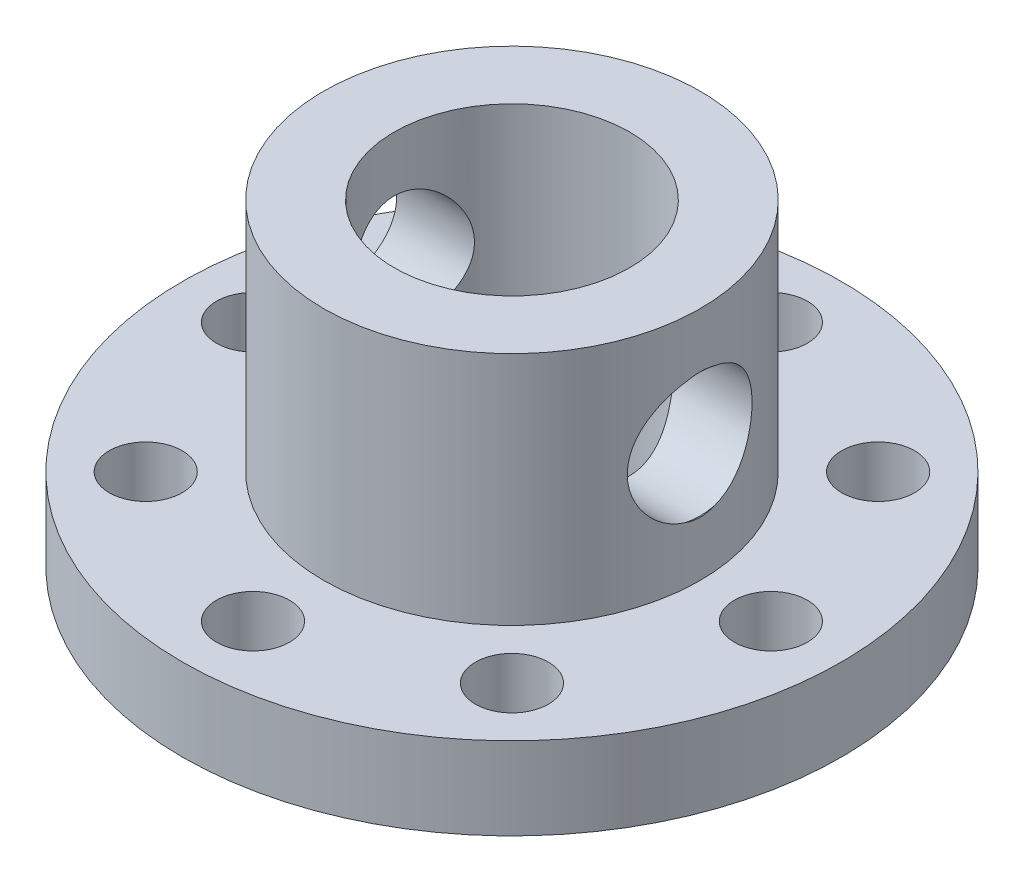
SolidWorks part; units mm, degrees
material "6061 Alloy"
ref_plane "Front Plane" through (0, 0, 0) normal (0, 0, 1) x (1, 0, 0)
ref_plane "Top Plane" through (0, 0, 0) normal (0, 1, 0) x (1, 0, 0)
ref_plane "Right Plane" through (0, 0, 0) normal (1, 0, 0) x (0, 0, -1)
sketch "Sketch1" plane through (0, 0, 0) normal (0, 1, 0) x (1, 0, 0)
  circle A0 centre (0, 0) radius 14
  dimension "D1" = 28
extrude "Boss-Extrude1" add sketch "Sketch1" along normal mid plane 3.5 contours A0
sketch "Sketch2" plane through (0, 1.75, 0) normal (0, 1, 0) x (1, 0, 0)
  line L0 (2.7822, 0.7455) -> (2.5435, 0.3349)
  line L1 (2.5435, 0.3349) -> (2.8804, 0)
  line L2 (2.8804, 0) -> (2.5435, -0.3349)
  line L3 (2.7822, -0.7455) -> (2.5435, -0.3349)
  line L4 (2.7822, -0.7455) -> (2.3701, -0.9817)
  line L5 (2.4945, -1.4402) -> (2.3701, -0.9817)
  line L6 (2.4945, -1.4402) -> (2.0353, -1.5617)
  line L7 (2.0367, -2.0367) -> (2.0353, -1.5617)
  line L8 (2.0367, -2.0367) -> (1.5617, -2.0353)
  line L9 (1.4402, -2.4945) -> (1.5617, -2.0353)
  line L10 (1.4402, -2.4945) -> (0.9817, -2.3701)
  line L11 (0.7455, -2.7822) -> (0.9817, -2.3701)
  line L12 (0.7455, -2.7822) -> (0.3349, -2.5435)
  line L13 (0, -2.8804) -> (0.3349, -2.5435)
  line L14 (0, -2.8804) -> (-0.3349, -2.5435)
  line L15 (-0.7455, -2.7822) -> (-0.3349, -2.5435)
  line L16 (-0.7455, -2.7822) -> (-0.9817, -2.3701)
  line L17 (-1.4402, -2.4945) -> (-0.9817, -2.3701)
  line L18 (-1.4402, -2.4945) -> (-1.5617, -2.0353)
  line L19 (-2.0367, -2.0367) -> (-1.5617, -2.0353)
  line L20 (-2.0367, -2.0367) -> (-2.0353, -1.5617)
  line L21 (-2.4945, -1.4402) -> (-2.0353, -1.5617)
  line L22 (-2.4945, -1.4402) -> (-2.3701, -0.9817)
  line L23 (-2.7822, -0.7455) -> (-2.3701, -0.9817)
  line L24 (-2.7822, -0.7455) -> (-2.5435, -0.3349)
  line L25 (-2.8804, 0) -> (-2.5435, -0.3349)
  line L26 (-2.8804, 0) -> (-2.5435, 0.3349)
  line L27 (-2.7822, 0.7455) -> (-2.5435, 0.3349)
  line L28 (-2.7822, 0.7455) -> (-2.3701, 0.9817)
  line L29 (-2.4945, 1.4402) -> (-2.3701, 0.9817)
  line L30 (-2.4945, 1.4402) -> (-2.0353, 1.5617)
  line L31 (-2.0367, 2.0367) -> (-2.0353, 1.5617)
  line L32 (-2.0367, 2.0367) -> (-1.5617, 2.0353)
  line L33 (-1.4402, 2.4945) -> (-1.5617, 2.0353)
  line L34 (-1.4402, 2.4945) -> (-0.9817, 2.3701)
  line L35 (-0.7455, 2.7822) -> (-0.9817, 2.3701)
  line L36 (-0.7455, 2.7822) -> (-0.3349, 2.5435)
  line L37 (0, 2.8804) -> (-0.3349, 2.5435)
  line L38 (0, 2.8804) -> (0.3349, 2.5435)
  line L39 (0.7455, 2.7822) -> (0.3349, 2.5435)
  line L40 (0.7455, 2.7822) -> (0.9817, 2.3701)
  line L41 (1.4402, 2.4945) -> (0.9817, 2.3701)
  line L42 (1.4402, 2.4945) -> (1.5617, 2.0353)
  line L43 (2.0367, 2.0367) -> (1.5617, 2.0353)
  line L44 (2.0367, 2.0367) -> (2.0353, 1.5617)
  line L45 (2.4945, 1.4402) -> (2.0353, 1.5617)
  line L46 (2.4945, 1.4402) -> (2.3701, 0.9817)
  line L47 (2.7822, 0.7455) -> (2.3701, 0.9817)
sketch "Sketch4" plane through (0, 1.75, 0) normal (0, 1, 0) x (1, 0, 0)
  circle A0 centre (0, 0) radius 5
  circle A1 centre (-7.7782, 7.7782) radius 1.025
  circle A2 centre (-7.7782, -7.7782) radius 1.025
  circle A3 centre (7.7782, -7.7782) radius 1.025
  circle A4 centre (7.7782, 7.7782) radius 1.025
  circle A5 centre (11, 0) radius 1.025
  circle A6 centre (0, -11) radius 1.025
  circle A7 centre (-11, 0) radius 1.025
  circle A8 centre (0, 11) radius 1.025
  circle A9 centre (0, 0) radius 14
hole_wizard "M2.5 Clearance Hole1" positions "Sketch5" profile "Sketch6" hole size "M2.5" standard "ANSI Metric"
sketch "Sketch5" plane through (0, 1.75, 0) normal (0, 1, 0) x (1, 0, 0)
  point P0 (-11, 0)
  point P3 (-7.7782, 7.7782)
  point P6 (0, 11)
  point P9 (7.7782, 7.7782)
  point P12 (11, 0)
  point P15 (7.7782, -7.7782)
  point P18 (0, -11)
  point P21 (-7.7782, -7.7782)
sketch "Sketch6" plane through (-11, 1.75, 0) normal (1, 0, 0) x (0, 0, 1)
  line L0 (0, 0) -> (0, 6.9313)
  line L1 (0, 6.9313) -> (1.55, 6)
  line L2 (1.55, 6) -> (1.55, 0)
  line L5 (1.55, 0) -> (0, 0)
  line L10 (0, 6.9313) -> (-1.55, 6) construction
  line L11 (0, -6.35) -> (0, 107.95) construction
  dimension "Hole Dia." = 3.1
  dimension "Hole Depth" = 6
  dimension "Drill Angle" = 118
sketch "Sketch7" plane through (0, -1.75, 0) normal (0, -1, 0) x (1, 0, 0)
  circle A0 centre (0, 0) radius 5
  dimension "D1" = 10
sketch "Sketch9" plane through (0, 1.75, 0) normal (0, 1, 0) x (1, 0, 0)
  circle A0 centre (0, 0) radius 8
  dimension "D1" = 16
extrude "Boss-Extrude2" add sketch "Sketch9" along normal blind 10
sketch "Sketch15" plane through (0, 11.75, 0) normal (0, 1, 0) x (1, 0, 0)
  circle A0 centre (0, 0) radius 5
  dimension "D1" = 10
extrude "Cut-Extrude-Thin1" [suppressed] cut sketch "Sketch15" against normal offset from surface (29 mm away) 4 thin
sketch "Sketch11" plane through (0, 11.75, 0) normal (0, 1, 0) x (1, 0, 0)
  circle A0 centre (0, 0) radius 16
  dimension "D1" = 32
extrude "Boss-Extrude3" [suppressed] add sketch "Sketch11" against normal blind 6
sketch "Sketch12" [suppressed] plane through (0, 34.75, 0) normal (0, 1, 0) x (1, 0, 0)
  line L1 (8, 8) -> (-8, 8) construction
  line L2 (8, 8) -> (8, -8) construction
  line L3 (8, -8) -> (-8, -8) construction
  line L4 (-8, 8) -> (-8, -8) construction
  line L5 (8, 8) -> (-8, -8) construction
  line L6 (8, -8) -> (-8, 8) construction
  point P0 (0, 0)
  dimension "D1" = 16
  dimension "D2" = 16
hole_wizard "Tap Drill for M4x0.7 Tap1" [suppressed] positions "Sketch13" profile "Sketch14" hole size "M4x0.7" standard "ANSI Metric"
sketch "Sketch13" [suppressed] plane through (0, 34.75, 0) normal (0, 1, 0) x (1, 0, 0)
  point P0 (-8, 8)
  point P3 (-8, -8)
  point P6 (8, -8)
  point P9 (8, 8)
sketch "Sketch14" plane through (-8, 34.75, -8) normal (1, 0, 0) x (0, 0, 1)
  line L0 (0, 0) -> (0, 36.5)
  line L1 (0, 36.5) -> (1.65, 36.5)
  line L2 (1.65, 36.5) -> (1.65, 0)
  line L5 (1.65, 0) -> (0, 0)
  line L11 (0, -6.35) -> (0, 107.95) construction
  dimension "Thru Hole Dia." = 3.3
  dimension "Thru Hole Depth" = 36.5
extrude "Cut-Extrude1" cut sketch "Sketch7" against normal through all contours A0
sketch "Sketch16" plane through (0, 0, 0) normal (1, 0, 0) x (0, 0, -1)
  line L0 (8, 11.75) -> (-8, 11.75) construction
  circle A0 centre (0, 6.75) radius 2
  dimension "D1" = 4
  dimension "D3" = 0
  dimension "D2" = 5
ref_plane "Plane1" through (8, 0, 0) normal (1, 0, 0) x (0, 0, -1)
sketch "Sketch22" plane through (8, 0, 0) normal (1, 0, 0) x (0, 0, -1)
  circle A0 centre (0, 6.75) radius 2
  dimension "D1" = 4
hole_wizard "M5 Clearance Hole1" positions "Sketch24" profile "Sketch25" hole size "M5" standard "ANSI Metric"
sketch "Sketch24" plane through (8, 0, 0) normal (1, 0, 0) x (0, 0, -1)
  point P0 (0, 6.75)
sketch "Sketch25" plane through (8, 6.75, 0) normal (0, 1, 0) x (0, 0, -1)
  line L0 (0, 0) -> (0, 26.9923)
  line L1 (0, 26.9923) -> (2.65, 25.4)
  line L2 (2.65, 25.4) -> (2.65, 0.025)
  line L3 (2.65, 0.025) -> (2.675, 0)
  line L5 (2.675, 0) -> (0, 0)
  line L6 (-2.65, 0.025) -> (-2.675, 0) construction
  line L10 (0, 26.9923) -> (-2.65, 25.4) construction
  line L11 (0, -6.35) -> (0, 107.95) construction
  dimension "Hole Dia." = 5.3
  dimension "Hole Depth" = 25.4
  dimension "Near C'Sink Dia." = 5.35
  dimension "Near C'Sink Angle" = 90
  dimension "Drill Angle" = 118
